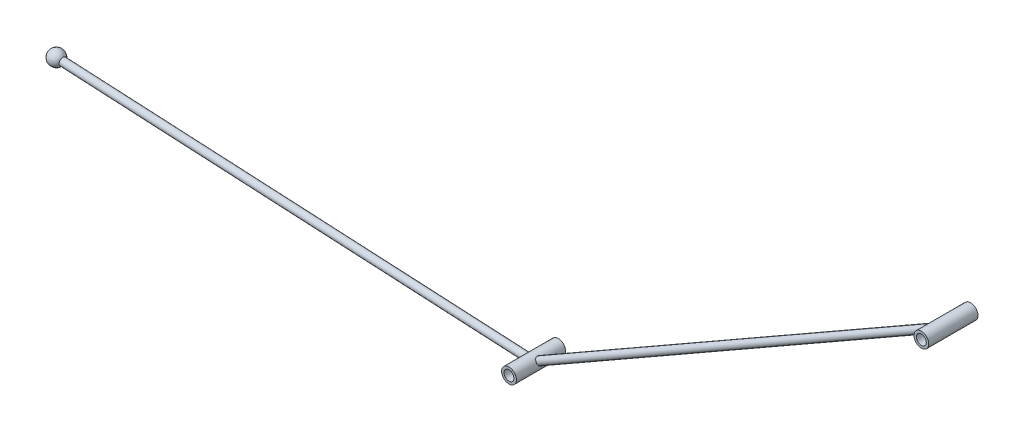
SolidWorks part; units mm, degrees
ref_plane "Plan de face" through (0, 0, 0) normal (0, 0, 1) x (1, 0, 0)
ref_plane "Plan de dessus" through (0, 0, 0) normal (0, 1, 0) x (1, 0, 0)
ref_plane "Plan de droite" through (0, 0, 0) normal (1, 0, 0) x (0, 0, -1)
sketch "Esquisse2" plane through (0, 0, 0) normal (0, 0, 1) x (1, 0, 0)
  line L0 (-291.1616, -154.3318) -> (-97.4173, -164.2892)
  line L1 (-97.4173, -164.2892) -> (71, -68)
  circle A3 centre (-291.1616, -154.3318) radius 3
  circle A4 centre (71, -68) radius 3
  dimension "D4" = 6
  dimension "D1" = 32.7
  dimension "D2" = 194
  dimension "D3" = 194
sketch "Esquisse3" plane through (0, 0, 0) normal (0, 0, 1) x (1, 0, 0)
  line L0 (-291.1616, -154.3318) -> (-97.4173, -164.2892)
  line L1 (-97.4173, -164.2892) -> (71, -68)
  line L2 (-97.4173, -164.2892) -> (71, -68) construction
ref_plane "Plan1" through (-291.1616, -154.3318, 0) normal (0.9987, -0.0513, 0) x (-0.0513, -0.9987, 0)
sketch "Esquisse4" plane through (-291.1616, -154.3318, 0) normal (0.9987, -0.0513, 0) x (-0.0513, -0.9987, 0)
  circle A0 centre (0, 0) radius 1.5
  dimension "D1" = 3
sweep "Balayage1" add profiles "Esquisse4" path "Esquisse3"
sketch "Esquisse5" plane through (0, 0, 0) normal (0, 0, 1) x (1, 0, 0)
  line L0 (-288.1655, -154.4858) -> (-294.1576, -154.1778) construction
  line L1 (-288.1655, -154.4858) -> (-294.1576, -154.1778)
  line L2 (-291.1616, -154.3318) -> (-97.4173, -164.2892) construction
  arc A0 (-288.1655, -154.4858) -> (-294.1576, -154.1778) centre (-291.1616, -154.3318) ccw
  dimension "D1" = 3
revolve "Révolution1" add sketch "Esquisse5" angle 360 about L0
sketch "Esquisse6" plane through (0, 0, 0) normal (0, 0, 1) x (1, 0, 0)
  circle A2 centre (-97.4173, -164.2892) radius 3
  circle A3 centre (70, -68) radius 3
  dimension "D1" = 6
extrude "Boss.-Extru.1" add sketch "Esquisse6" along normal mid plane 20
sketch "Esquisse7" plane through (0, 0, 10) normal (0, 0, 1) x (1, 0, 0)
  circle A2 centre (-97.4173, -164.2892) radius 2
  circle A3 centre (-97.4173, -164.2892) radius 2
  circle A5 centre (70, -68) radius 2
  circle A6 centre (70, -68) radius 2
  dimension "D1" = 1
  dimension "D2" = 1
extrude "Enlèv. mat.-Extru.1" cut sketch "Esquisse7" against normal through all
